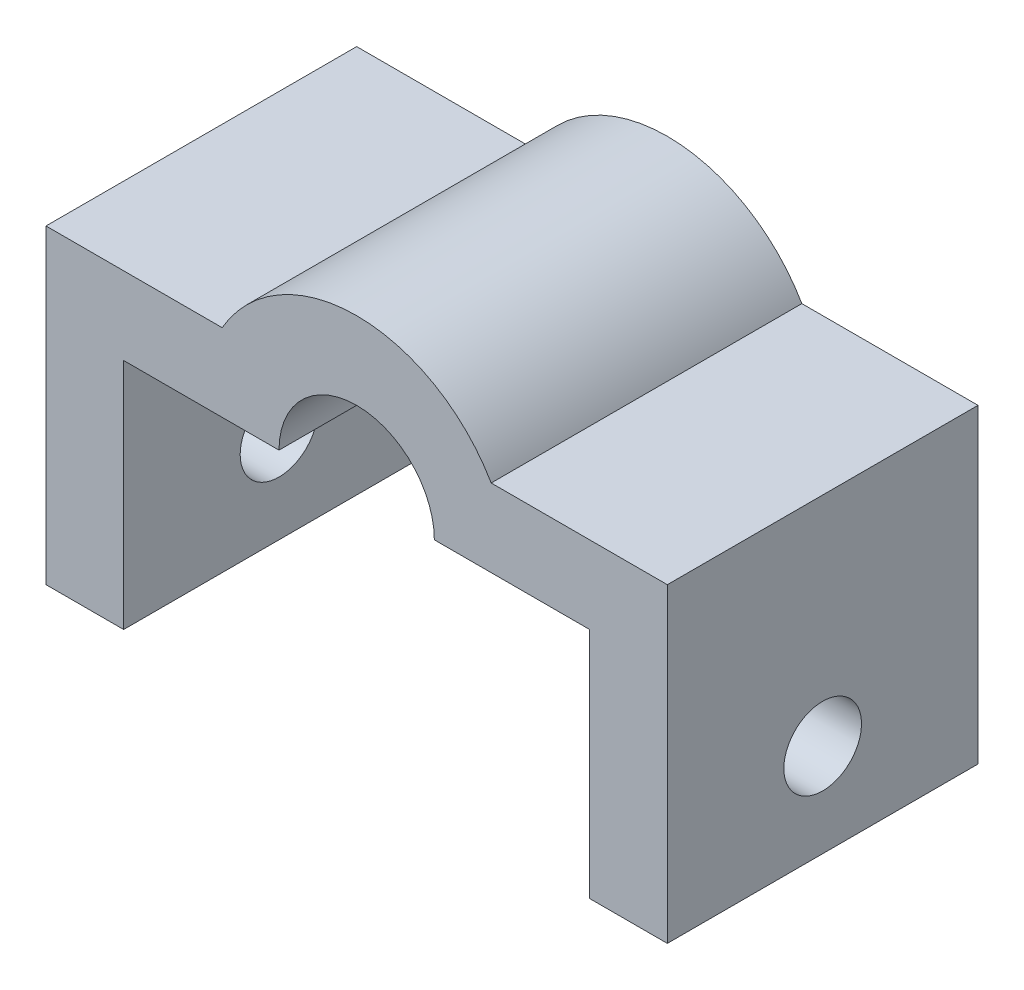
SolidWorks part; units mm, degrees
ref_plane "Front Plane" through (0, 0, 0) normal (0, 0, 1) x (1, 0, 0)
ref_plane "Top Plane" through (0, 0, 0) normal (0, 1, 0) x (1, 0, 0)
ref_plane "Right Plane" through (0, 0, 0) normal (1, 0, 0) x (0, 0, -1)
sketch "Sketch1" plane through (0, 0, 0) normal (0, 0, 1) x (1, 0, 0)
  line L0 (0, 0) -> (0, 9.525)
  line L1 (0, 9.525) -> (6.35, 9.525)
  line L2 (12.7, 9.525) -> (19.05, 9.525)
  line L3 (19.05, 9.525) -> (19.05, 0)
  line L5 (19.05, 0) -> (22.225, 0)
  line L6 (22.225, 0) -> (22.225, 12.7)
  line L7 (22.225, 12.7) -> (15.0243, 12.7)
  line L8 (0, 0) -> (-3.175, 0)
  line L9 (-3.175, 0) -> (-3.175, 12.7)
  line L10 (-3.175, 12.7) -> (4.0257, 12.7)
  arc A0 (12.7, 9.525) -> (6.35, 9.525) centre (9.525, 9.525) ccw
  arc A1 (15.0243, 12.7) -> (4.0257, 12.7) centre (9.525, 9.525) ccw
  dimension "D2" = 3.175
  dimension "D8" = 3.175
  dimension "D1" = 19.05
  dimension "D3" = 3.175
  dimension "D4" = 3.175
  dimension "D5" = 12.7
  dimension "D6" = 12.7
  dimension "D7" = 3.175
  dimension "D9" = 12.7
  dimension "D10" = 12.7
extrude "Boss-Extrude1" add sketch "Sketch1" along normal blind 12.7 contours L10 A1 L7 L6 L5 L3 L2 A0 L1 L0 L8 L9
sketch "Sketch2" plane through (-3.175, 0, 0) normal (-1, 0, 0) x (0, 0, 1)
  line L0 (0, 0) -> (0, 12.7) construction
  line L1 (12.7, 0) -> (0, 0) construction
  circle A0 centre (6.35, 3.81) radius 1.5875
  point P6 (6.35, 3.81)
  dimension "D1" = 3.175
  dimension "D2" = 6.35
  dimension "D3" = 3.81
extrude "Cut-Extrude1" cut sketch "Sketch2" against normal blind 76.2 contours A0
